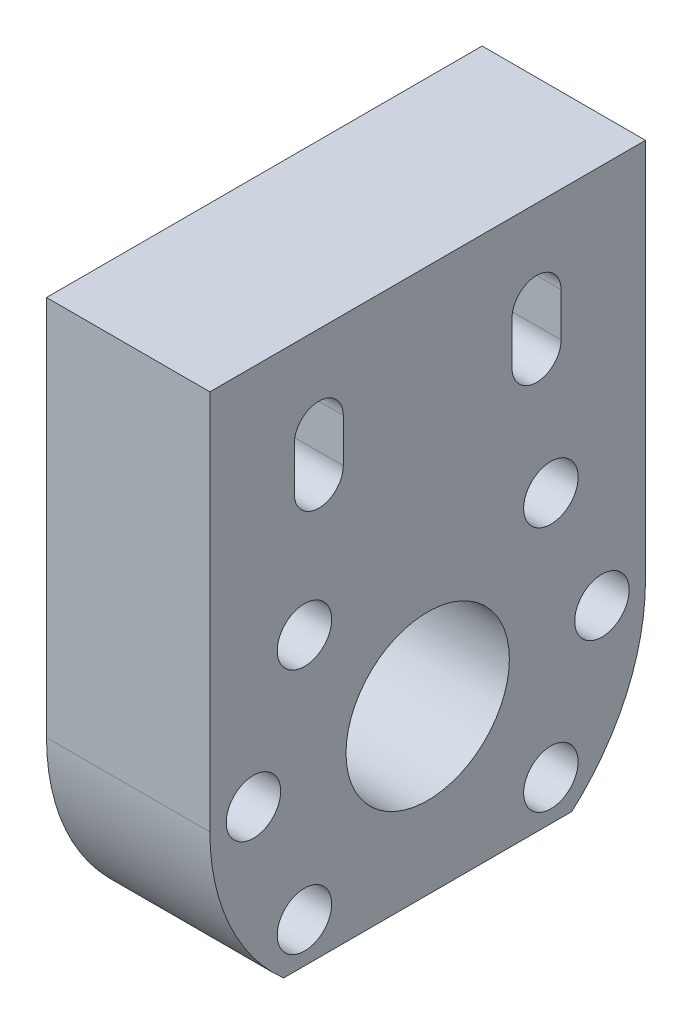
SolidWorks part; units mm, degrees
ref_plane "Front Plane" through (0, 0, 0) normal (0, 0, 1) x (1, 0, 0)
ref_plane "Top Plane" through (0, 0, 0) normal (0, 1, 0) x (1, 0, 0)
ref_plane "Right Plane" through (0, 0, 0) normal (1, 0, 0) x (0, 0, -1)
sketch "Sketch1" plane through (0, 0, 0) normal (1, 0, 0) x (0, 0, -1)
  line L0 (-13.2288, -15) -> (13.2288, -15)
  line L1 (0, 55) -> (0, -55) construction
  line L3 (-20, 0) -> (-20, 35)
  line L4 (-20, 35) -> (20, 35)
  line L5 (20, 0) -> (20, 35)
  line L7 (-12.25, 23) -> (-12.25, 27)
  line L9 (-7.75, 23) -> (-7.75, 27)
  line L10 (12.25, 23) -> (12.25, 27)
  line L11 (7.75, 23) -> (7.75, 27)
  circle A1 centre (0, 0) radius 7.5
  arc A3 (-13.2288, -15) -> (-20, 0) centre (0, 0) cw
  arc A4 (20, 0) -> (13.2288, -15) centre (0, 0) cw
  circle A6 centre (16, 0) radius 2.5
  circle A13 centre (11.3137, -11.3137) radius 2.5
  circle A15 centre (-11.3137, -11.3137) radius 2.5
  circle A16 centre (-16, 0) radius 2.5
  circle A17 centre (-11.3137, 11.3137) radius 2.5
  circle A19 centre (11.3137, 11.3137) radius 2.5
  circle A20 centre (0, 16) radius 2.5 [skipped]
  circle A21 centre (0, -16) radius 2.5 [skipped]
  arc A24 (-12.25, 27) -> (-7.75, 27) centre (-10, 27) cw
  arc A25 (-7.75, 23) -> (-12.25, 23) centre (-10, 23) cw
  arc A26 (12.25, 27) -> (7.75, 27) centre (10, 27) ccw
  arc A27 (7.75, 23) -> (12.25, 23) centre (10, 23) ccw
  point P5 (0, -15)
  point P29 (0, 0)
  dimension "D1" = 20
  dimension "D3" = 15
  dimension "D6" = 20
  dimension "D7" = 23
  dimension "D8" = 5
  dimension "D9" = 8
  dimension "D2" = 15
  dimension "D4" = 40
  dimension "D5" = 50
  dimension "D13" = 4.5
  dimension "D14" = 4
extrude "Boss-Extrude1" add sketch "Sketch1" along normal blind 15
